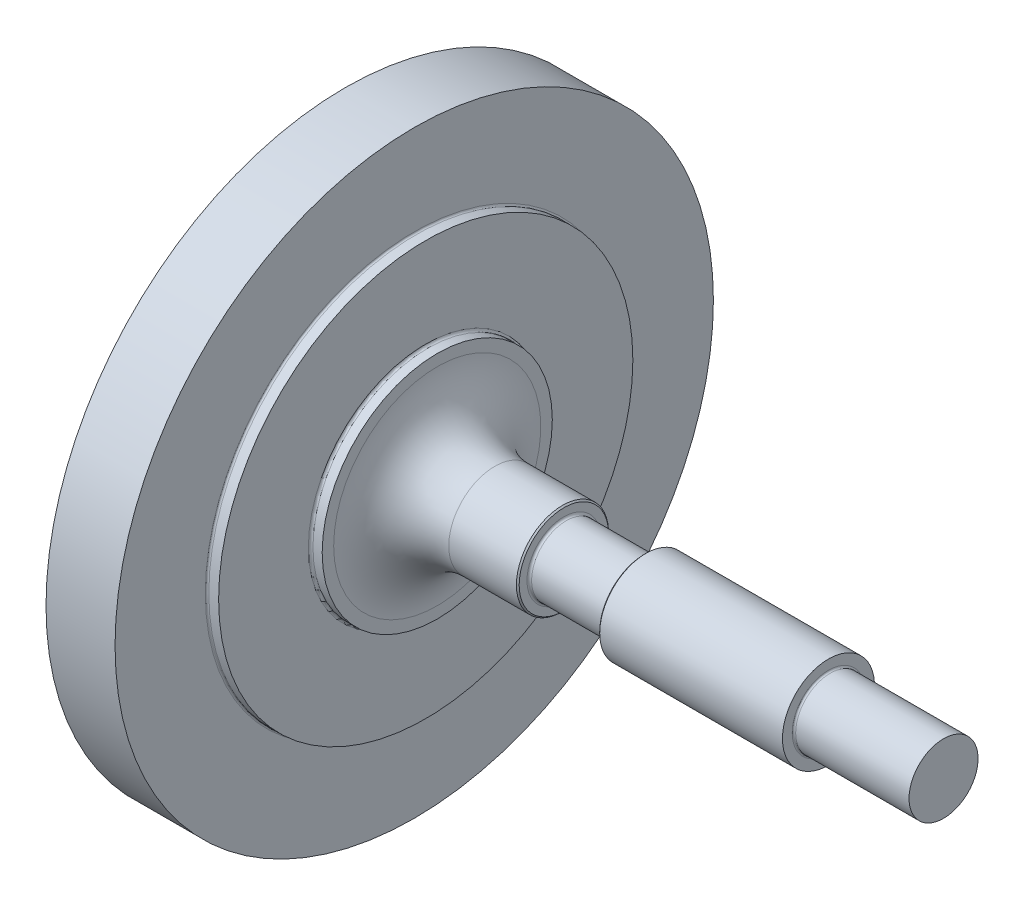
SolidWorks part; units mm, degrees
ref_plane "Plane1" through (0, 0, 0) normal (0, 0, 1) x (1, 0, 0)
ref_plane "Plane2" through (0, 0, 0) normal (0, 1, 0) x (1, 0, 0)
ref_plane "Plane3" through (0, 0, 0) normal (1, 0, 0) x (0, 0, -1)
sketch "Sketch2" plane through (0, 0, 0) normal (0, 0, 1) x (1, 0, 0)
  line L0 (-25.019, 7.62) -> (0, 7.62)
  line L1 (-25.4, 8.001) -> (-25.4, 10.16)
  line L2 (-25.4, 10.16) -> (-66.04, 10.16)
  line L3 (-66.04, 10.16) -> (-66.04, 8.128)
  line L4 (-66.548, 7.62) -> (-83.312, 7.62)
  line L5 (-83.82, 8.128) -> (-83.82, 10.16)
  line L6 (-83.82, 10.16) -> (-99.06, 10.16)
  line L7 (-111.76, 25.4) -> (-111.76, 22.86)
  line L8 (12.7, 0) -> (22.86, 0) construction
  line L10 (-111.76, 25.4) -> (-113.792, 25.4)
  line L11 (-114.3, 25.908) -> (-114.3, 45.72)
  line L12 (-114.3, 45.72) -> (-116.459, 45.72)
  line L13 (-116.84, 46.101) -> (-116.84, 66.04)
  line L14 (-116.84, 66.04) -> (-132.08, 66.04)
  line L15 (-132.08, 66.04) -> (-132.08, 46.228)
  line L16 (-132.588, 45.72) -> (-134.62, 45.72)
  line L17 (-134.62, 45.72) -> (-134.62, 25.908)
  line L18 (-135.128, 25.4) -> (-137.16, 25.4)
  line L19 (-137.16, 25.4) -> (-137.16, 8.128)
  line L20 (-137.668, 7.62) -> (-142.24, 7.62)
  line L21 (-142.24, 7.62) -> (-142.24, 0)
  line L22 (-142.24, 0) -> (0, 0)
  line L23 (0, 0) -> (0, 7.62)
  arc A0 (-111.76, 22.86) -> (-99.06, 10.16) centre (-99.06, 22.86) ccw
  arc A1 (-25.4, 8.001) -> (-25.019, 7.62) centre (-25.019, 8.001) ccw
  arc A2 (-116.459, 45.72) -> (-116.84, 46.101) centre (-116.459, 46.101) cw
  arc A3 (-114.3, 25.908) -> (-113.792, 25.4) centre (-113.792, 25.908) ccw
  arc A4 (-137.16, 8.128) -> (-137.668, 7.62) centre (-137.668, 8.128) cw
  arc A5 (-135.128, 25.4) -> (-134.62, 25.908) centre (-135.128, 25.908) ccw
  arc A6 (-132.588, 45.72) -> (-132.08, 46.228) centre (-132.588, 46.228) ccw
  arc A7 (-83.312, 7.62) -> (-83.82, 8.128) centre (-83.312, 8.128) cw
  arc A8 (-66.548, 7.62) -> (-66.04, 8.128) centre (-66.548, 8.128) ccw
  dimension "D1" = 12.7
  dimension "D2" = 0.381
  dimension "D3" = 0.381
  dimension "D4" = 0.508
  dimension "D5" = 0.508
  dimension "D6" = 0.508
revolve "Base-Revolve" add sketch "Sketch2" angle 360 about L8
sketch "Sketch3" plane through (0, 0, 0) normal (0, 0, 1) x (1, 0, 0)
  line L0 (-144.78, 0) -> (-144.78, 8.8886)
  line L1 (-133.932, 71.12) -> (-141.1848, 17.5684)
  line L2 (-144.1811, 11.2815) -> (-141.7377, 15.8573)
  line L7 (-133.932, 71.12) -> (-115.7514, 71.12)
  line L8 (-115.7514, 71.12) -> (-105.4307, 34.9975)
  line L9 (0.1676, 13.882) -> (-81.846, 16.5892)
  line L16 (5.08, 8.8048) -> (5.08, 0)
  line L17 (5.08, 0) -> (-144.78, 0)
  arc A0 (-81.846, 16.5892) -> (-105.4307, 34.9975) centre (-81.008, 41.9754) cw
  arc A1 (0.1676, 13.882) -> (5.08, 8.8048) centre (0, 8.8048) cw
  arc A2 (-144.1811, 11.2815) -> (-144.78, 8.8886) centre (-139.7, 8.8886) ccw
  arc A3 (-141.1848, 17.5684) -> (-141.7377, 15.8573) centre (-146.2189, 18.2502) cw
  dimension "D1" = 25.4
  dimension "D2" = 5.08
  dimension "D3" = 5.08
chamfer "Chamfer1" distance 0.3048 angle 45
